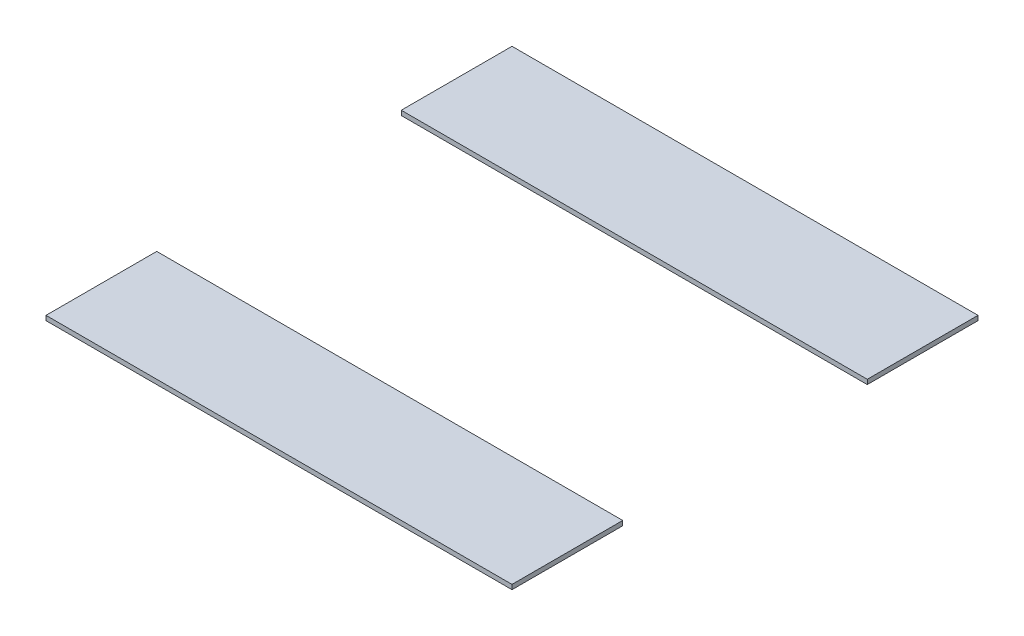
SolidWorks part; units mm, degrees
material "6061-T6 (SS)"
ref_plane "Alzado" through (0, 0, 0) normal (0, 0, 1) x (1, 0, 0)
ref_plane "Planta" through (0, 0, 0) normal (0, 1, 0) x (1, 0, 0)
ref_plane "Vista lateral" through (0, 0, 0) normal (1, 0, 0) x (0, 0, -1)
sketch "Sketch1" plane through (0, 0, 0) normal (0, 1, 0) x (1, 0, 0)
  line L1 (-101, 101) -> (101, 101)
  line L2 (-101, 101) -> (-101, -101)
  line L3 (-101, -101) -> (101, -101)
  line L4 (101, 101) -> (101, -101)
  line L5 (-101, 101) -> (101, -101) construction
  line L6 (-101, -101) -> (101, 101) construction
  point P0 (0, 0)
  dimension "D1" = 202
  dimension "D2" = 202
extrude "Boss-Extrude1" add sketch "Sketch1" along normal blind 2
sketch "Sketch2" plane through (0, 0, 0) normal (0, 1, 0) x (1, 0, 0)
  line L0 (101, -101) -> (101, 101) construction
  line L1 (-101, 53) -> (101, 53)
  line L2 (-101, 53) -> (-101, -53)
  line L3 (-101, -53) -> (101, -53)
  line L4 (101, 53) -> (101, -53)
  line L5 (-101, 53) -> (101, -53) construction
  line L6 (-101, -53) -> (101, 53) construction
  point P0 (0, 0)
  dimension "D1" = 106
extrude "Cut-Extrude2" cut sketch "Sketch2" along normal blind 2
